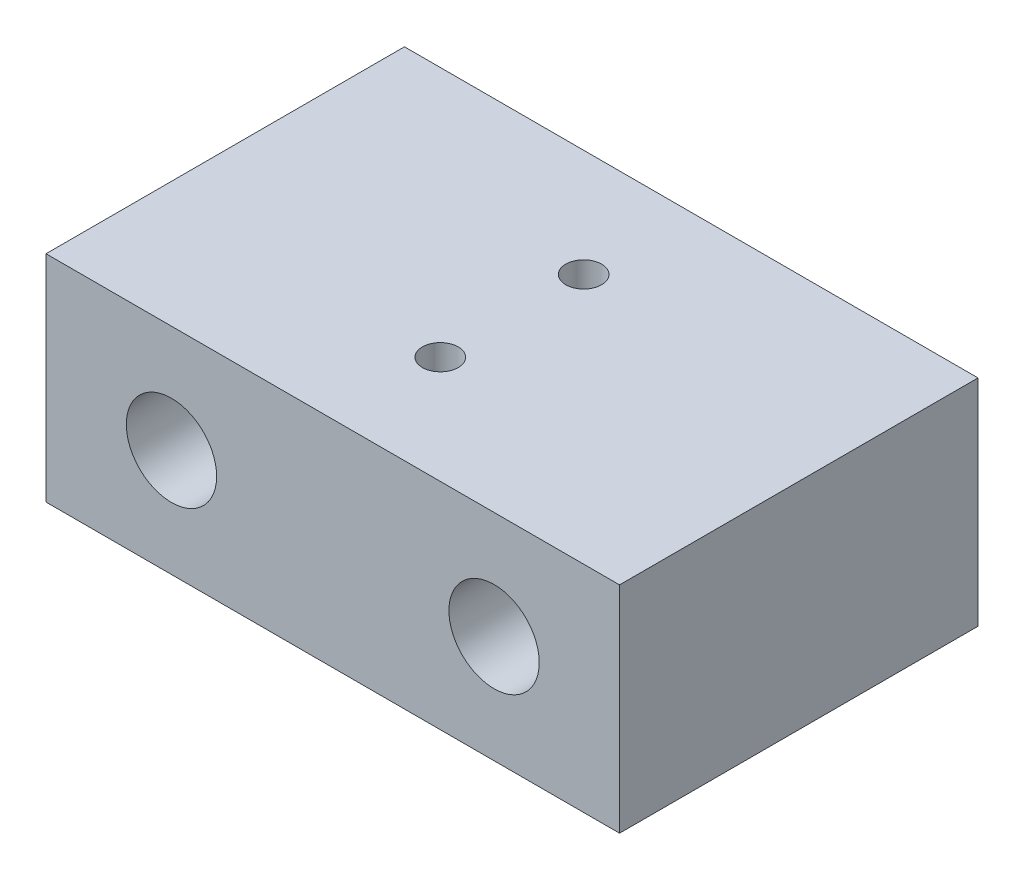
SolidWorks part; units mm, degrees
ref_plane "Front Plane" through (0, 0, 0) normal (0, 0, 1) x (1, 0, 0)
ref_plane "Top Plane" through (0, 0, 0) normal (0, 1, 0) x (1, 0, 0)
ref_plane "Right Plane" through (0, 0, 0) normal (1, 0, 0) x (0, 0, -1)
sketch "Sketch1" plane through (0, 0, 0) normal (0, 0, 1) x (1, 0, 0)
  line L0 (-14.2875, 0) -> (14.2875, 0) construction
  line L1 (-25.4, -9.525) -> (25.4, -9.525)
  line L2 (-25.4, -9.525) -> (-25.4, 9.525)
  line L3 (-25.4, 9.525) -> (25.4, 9.525)
  line L4 (25.4, -9.525) -> (25.4, 9.525)
  line L5 (-25.4, -9.525) -> (25.4, 9.525) construction
  line L6 (-25.4, 9.525) -> (25.4, -9.525) construction
  circle A0 centre (-14.2875, 0) radius 4
  circle A1 centre (14.2875, 0) radius 4
  point P0 (0, 0)
  point P10 (0, 0)
  dimension "D3" = 8
  dimension "D4" = 8
  dimension "D1" = 19.05
  dimension "D2" = 50.8
  dimension "D5" = 28.575
extrude "Boss-Extrude1" add sketch "Sketch1" along normal blind 31.75
sketch "Sketch2" plane through (0, 9.525, 0) normal (0, 1, 0) x (1, 0, 0)
  line L0 (0, -9.525) -> (0, -22.225) construction
  line L1 (-25.4, -31.75) -> (-25.4, 0) construction
  circle A0 centre (0, -9.525) radius 1.5875
  circle A1 centre (0, -22.225) radius 1.5875
  point P4 (-25.4, -15.875)
  point P7 (0, -15.875)
  dimension "D1" = 3.175
  dimension "D2" = 3.175
  dimension "D3" = 12.7
extrude "Cut-Extrude1" cut sketch "Sketch2" against normal through all
